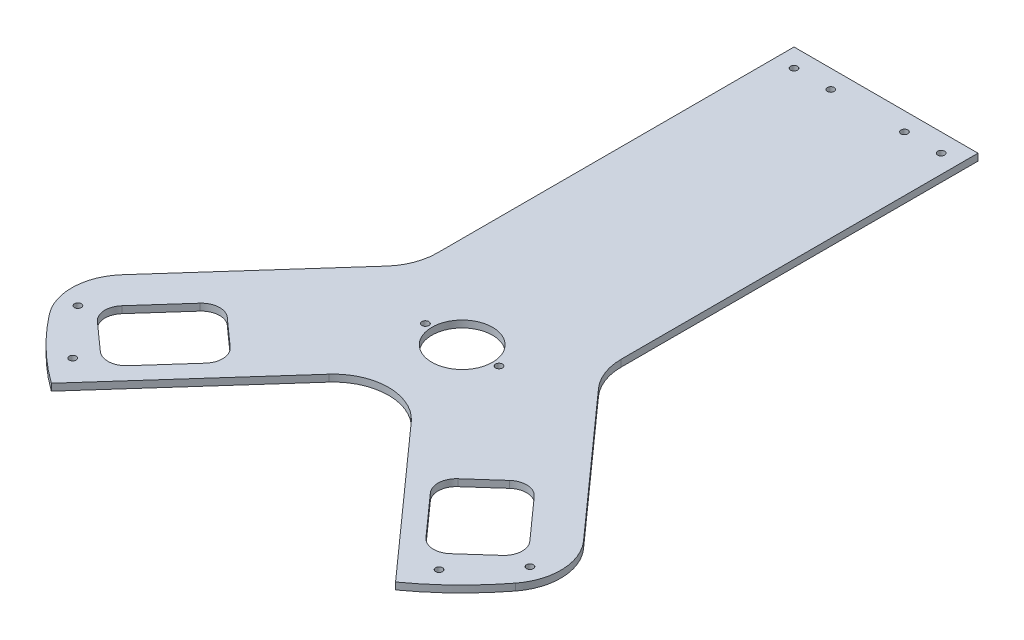
SolidWorks part; units mm, degrees
ref_plane "Front Plane" through (0, 0, 0) normal (0, 0, 1) x (1, 0, 0)
ref_plane "Top Plane" through (0, 0, 0) normal (0, 1, 0) x (1, 0, 0)
ref_plane "Right Plane" through (0, 0, 0) normal (1, 0, 0) x (0, 0, -1)
sketch "Sketch1" plane through (0, 0, 0) normal (0, 1, 0) x (1, 0, 0)
  line L0 (-63.5, 31.75) -> (-178.5164, -97.0677)
  line L1 (-215.9, 31.75) -> (215.9, 31.75)
  line L2 (-215.9, 31.75) -> (-215.9, -31.75)
  line L3 (-215.9, -31.75) -> (215.9, -31.75)
  line L4 (215.9, 31.75) -> (215.9, -31.75)
  line L5 (-215.9, 31.75) -> (215.9, -31.75) construction
  line L6 (-215.9, -31.75) -> (215.9, 31.75) construction
  line L7 (63.5, 31.75) -> (-63.5, 31.75)
  line L8 (63.5, 31.75) -> (63.5, 292.608)
  line L9 (63.5, 292.608) -> (-63.5, 292.608)
  line L10 (-63.5, 31.75) -> (-63.5, 292.608)
  line L11 (0, -31.75) -> (-118.8264, -164.8348)
  line L12 (0, -31.75) -> (118.8264, -164.8348)
  line L13 (63.5, 31.75) -> (178.5164, -97.0677)
  circle A0 centre (0, 0) radius 20.955
  circle A1 centre (0, 0) radius 25.4 construction
  circle A2 centre (-25.4, 0) radius 2.3813
  circle A3 centre (25.4, 0) radius 2.3812
  circle A4 centre (0, 0) radius 203.2
  point P0 (0, 0)
  point P23 (-117.0335, -166.1126)
  point P24 (118.8376, -166.1126)
  dimension "D5" = 4.7625
  dimension "D6" = 4.7625
  dimension "D7" = 41.91
  dimension "D8" = 50.8
  dimension "D10" = 406.4
  dimension "D1" = 431.8
  dimension "D2" = 63.5
  dimension "D3" = 127
  dimension "D4" = 63.5
  dimension "D9" = 260.858
  dimension "D11" = 59.69
  dimension "D12" = 59.69
extrude "Boss-Extrude1" add sketch "Sketch1" along normal blind 4.7625 contours L10 L1 L8 L9 | L4 L1 L2 L3 A3 A2 A0 | L0 A4 L11 L3 | L12 A4 L13 L3 | A4 L8 L9 L10
sketch "Sketch2" plane through (0, 4.7625, 0) normal (0, 1, 0) x (1, 0, 0)
  line L0 (0, 292.608) -> (0, -31.75) construction
  line L1 (63.5, 292.608) -> (-63.5, 292.608) construction
  circle A0 centre (25.4, 279.908) radius 2.3813
  circle A1 centre (50.8, 279.908) radius 2.3813
  circle A2 centre (-50.8, 279.908) radius 2.3813
  circle A3 centre (-25.4, 279.908) radius 2.3813
  point P8 (0, -48.4413)
  point P14 (0, 0)
  point P15 (0, 0)
  dimension "D3" = 4.7625
  dimension "D4" = 4.7625
  dimension "D1" = 25.4
  dimension "D2" = 50.8
  dimension "D5" = 12.7
  dimension "D6" = 12.7
extrude "Cut-Extrude1" cut sketch "Sketch2" against normal through all
fillet "Fillet1" radius 38.1 3 edges at (63.5, 2.3813, -31.75) (-63.5, 2.3813, -31.75) (0, 2.3813, 31.75)
sketch "Sketch4" plane through (0, 4.7625, 0) normal (0, 1, 0) x (1, 0, 0)
  line L0 (0, 292.608) -> (0, 0) construction
  line L1 (63.5, 292.608) -> (-63.5, 292.608) construction
  line L2 (0, 0) -> (-156.0485, -109.2663) construction
  line L3 (0, 0) -> (0, -190.5) construction
  circle A0 centre (0, 0) radius 190.5 construction
  circle A1 centre (-156.0485, -109.2663) radius 2.3813
  circle A2 centre (-126.4791, -142.4545) radius 2.3813
  circle A3 centre (126.4791, -142.4545) radius 2.3813
  circle A4 centre (156.0485, -109.2663) radius 2.3813
  dimension "D1" = 381
  dimension "D4" = 4.7625
  dimension "D5" = 4.7625
  dimension "D2" = 44.45
  dimension "D3" = 55
extrude "Cut-Extrude3" cut sketch "Sketch4" against normal through all
fillet "Fillet2" radius 38.1 2 edges at (178.5164, 2.3813, 97.0677) (-178.5164, 2.3813, 97.0677)
sketch "Sketch5" plane through (0, 4.7625, 0) normal (0, 1, 0) x (1, 0, 0)
  line L0 (-149.2765, -103.5959) -> (-111.3829, -137.4296)
  line L1 (-149.2765, -103.5959) -> (-106.9843, -56.229)
  line L2 (-111.3829, -137.4296) -> (-69.0908, -90.0627)
  line L3 (-106.9843, -56.229) -> (-69.0908, -90.0627)
  line L8 (-28.4202, -63.5804) -> (-118.8264, -164.8348) construction
  line L9 (0, 292.608) -> (0, 0) construction
  line L10 (63.5, 292.608) -> (-63.5, 292.608) construction
  line L11 (106.9843, -56.229) -> (69.0908, -90.0627)
  line L12 (111.3829, -137.4296) -> (69.0908, -90.0627)
  line L13 (149.2765, -103.5959) -> (106.9843, -56.229)
  line L14 (149.2765, -103.5959) -> (111.3829, -137.4296)
  dimension "D1" = 50.8
  dimension "D2" = 12.7
  dimension "D3" = 63.5
  dimension "D4" = 25.4
extrude "Cut-Extrude4" cut sketch "Sketch5" against normal through all
fillet "Fillet3" radius 12.7 8 edges at (111.3829, 2.3813, 137.4296) (69.0908, 2.3813, 90.0627) (106.9843, 2.3813, 56.229) (149.2765, 2.3813, 103.5959) (-69.0908, 2.3813, 90.0627) (-106.9843, 2.3813, 56.229) (-149.2765, 2.3813, 103.5959) (-111.3829, 2.3813, 137.4296)
